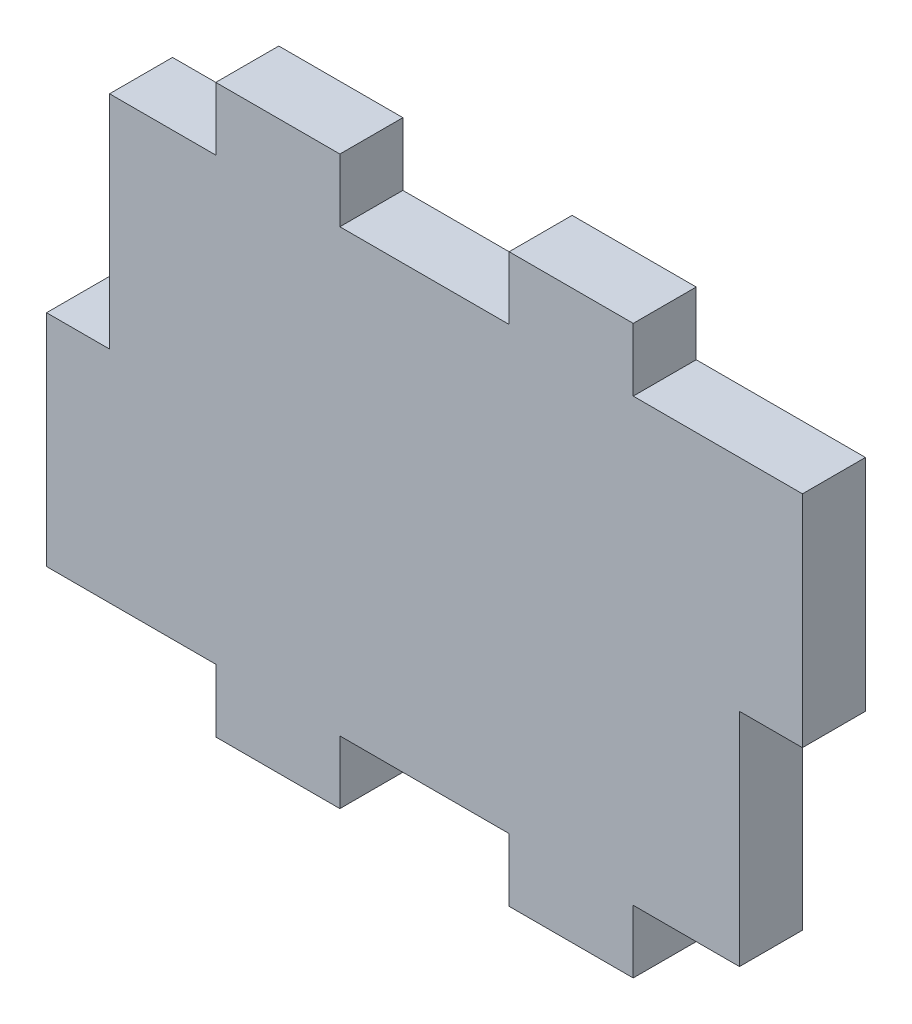
SolidWorks part; units mm, degrees
ref_plane "Front Plane" through (0, 0, 0) normal (0, 0, 1) x (1, 0, 0)
ref_plane "Top Plane" through (0, 0, 0) normal (0, 1, 0) x (1, 0, 0)
ref_plane "Right Plane" through (0, 0, 0) normal (1, 0, 0) x (0, 0, -1)
sketch "Sketch2" plane through (0, 0, 0) normal (0, 0, 1) x (1, 0, 0)
  line L0 (-16.5667, 22.5) -> (-16.5667, 17.5)
  line L1 (-25, -17.5) -> (25, -17.5)
  line L2 (-25, -17.5) -> (-25, 17.5)
  line L3 (-25, 17.5) -> (25, 17.5)
  line L4 (25, -17.5) -> (25, 17.5)
  line L5 (-25, -17.5) -> (25, 17.5) construction
  line L6 (-25, 17.5) -> (25, -17.5) construction
  line L7 (-25, -17.5) -> (-30, -17.5)
  line L8 (-25, -17.5) -> (-25, -0.05)
  line L9 (-25, -0.05) -> (-30, -0.05)
  line L10 (-30, -17.5) -> (-30, -0.05)
  line L11 (-16.5667, -17.5) -> (-6.7167, -17.5)
  line L12 (-16.5667, -17.5) -> (-16.5667, -22.5)
  line L13 (-16.5667, -22.5) -> (-6.7167, -22.5)
  line L14 (-6.7167, -17.5) -> (-6.7167, -22.5)
  line L19 (6.7167, -17.5) -> (16.5667, -17.5)
  line L20 (6.7167, -17.5) -> (6.7167, -22.5)
  line L21 (6.7167, -22.5) -> (16.5667, -22.5)
  line L22 (16.5667, -17.5) -> (16.5667, -22.5)
  line L23 (25, 17.5) -> (30, 17.5)
  line L24 (25, 17.5) -> (25, 0.05)
  line L25 (25, 0.05) -> (30, 0.05)
  line L26 (30, 17.5) -> (30, 0.05)
  line L27 (-16.5667, 22.5) -> (-6.7167, 22.5)
  line L28 (-6.7167, 22.5) -> (-6.7167, 17.5)
  line L29 (-16.5667, 17.5) -> (-6.7167, 17.5)
  line L34 (6.7167, 22.5) -> (6.7167, 17.5)
  line L35 (6.7167, 22.5) -> (16.5667, 22.5)
  line L36 (16.5667, 22.5) -> (16.5667, 17.5)
  line L37 (6.7167, 17.5) -> (16.5667, 17.5)
  line L38 (6.7167, -20) -> (-6.7167, -20) construction
  line L42 (16.5667, -20) -> (30, -20) construction
  line L43 (30, -20) -> (30, 0.05) construction
  line L44 (-16.5667, -20) -> (-30, -20) construction
  line L45 (-30, -20) -> (-30, -17.5) construction
  point P0 (0, 0)
  dimension "D1" = 35
  dimension "D2" = 50
  dimension "D3" = 17.45
  dimension "D4" = 5
  dimension "D5" = 5
  dimension "D7" = 5
  dimension "D8" = 9.85
  dimension "D10" = 9.85
  dimension "D13" = 5
  dimension "D14" = 17.45
  dimension "D16" = 2
extrude "Boss-Extrude1" add sketch "Sketch2" along normal blind 5
